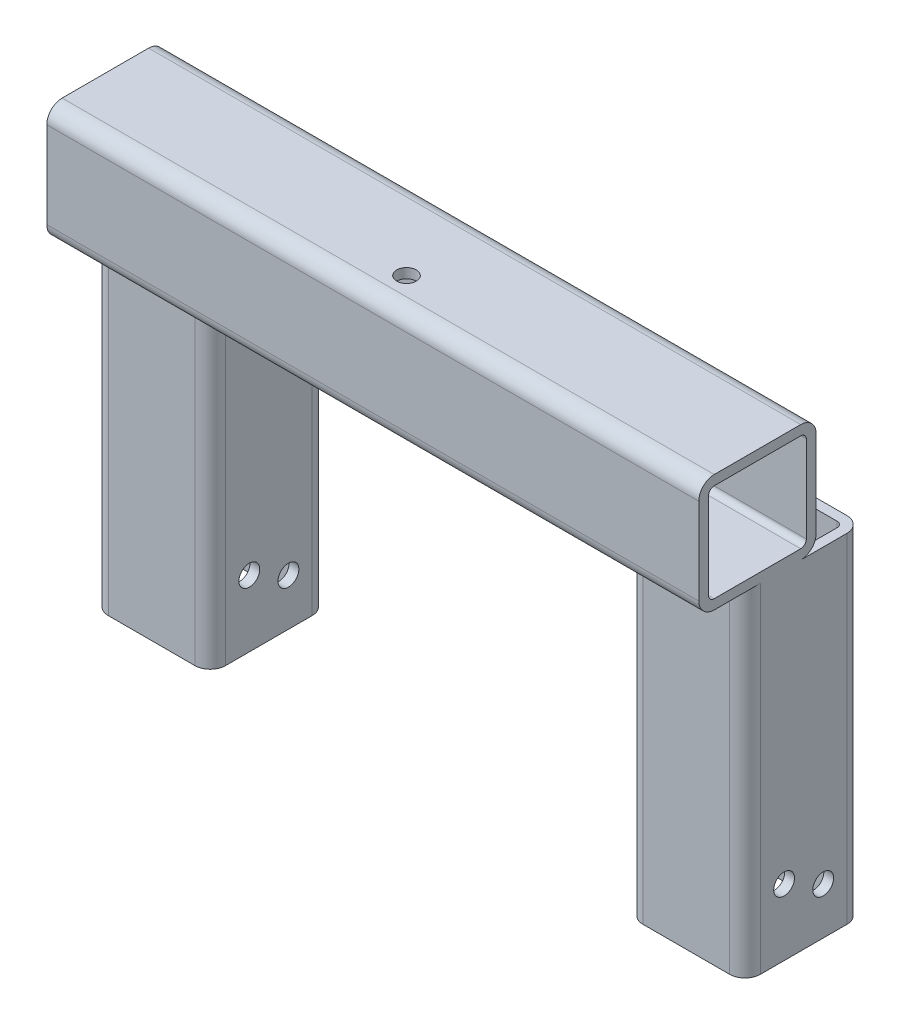
SolidWorks part; units mm, degrees
ref_plane "Front Plane" through (0, 0, 0) normal (0, 0, 1) x (1, 0, 0)
ref_plane "Top Plane" through (0, 0, 0) normal (0, 1, 0) x (1, 0, 0)
ref_plane "Right Plane" through (0, 0, 0) normal (1, 0, 0) x (0, 0, -1)
sketch "Sketch1" plane through (0, 0, 0) normal (0, 1, 0) x (1, 0, 0)
  line L0 (-14.05, 19.05) -> (14.05, 19.05)
  line L1 (19.05, 14.05) -> (19.05, -14.05)
  line L2 (-15.875, 14.05) -> (-15.875, -14.05)
  line L3 (-14.05, -15.875) -> (14.05, -15.875)
  line L4 (14.05, -19.05) -> (-14.05, -19.05)
  line L5 (-19.05, -14.05) -> (-19.05, 14.05)
  line L6 (0, 19.05) -> (0, -19.05) construction
  line L7 (-19.05, 0) -> (19.05, 0) construction
  line L8 (15.875, -14.05) -> (15.875, 14.05)
  line L9 (14.05, 15.875) -> (-14.05, 15.875)
  line L10 (0, 15.875) -> (0, -15.875) construction
  line L11 (-15.875, 0) -> (15.875, 0) construction
  arc A0 (14.05, 19.05) -> (19.05, 14.05) centre (14.05, 14.05) cw
  arc A1 (19.05, -14.05) -> (14.05, -19.05) centre (14.05, -14.05) cw
  arc A2 (-14.05, -19.05) -> (-19.05, -14.05) centre (-14.05, -14.05) cw
  arc A3 (-19.05, 14.05) -> (-14.05, 19.05) centre (-14.05, 14.05) cw
  arc A4 (-15.875, -14.05) -> (-14.05, -15.875) centre (-14.05, -14.05) ccw
  arc A5 (14.05, -15.875) -> (15.875, -14.05) centre (14.05, -14.05) ccw
  arc A6 (15.875, 14.05) -> (14.05, 15.875) centre (14.05, 14.05) ccw
  arc A7 (-14.05, 15.875) -> (-15.875, 14.05) centre (-14.05, 14.05) ccw
  point P33 (0, 0)
  dimension "D1" = 5
  dimension "D2" = 3.175
  dimension "D3" = 38.1
extrude "Boss-Extrude1" add sketch "Sketch1" along normal blind 110
ref_plane "Plane1" through (86.85, 0, 0) normal (1, 0, 0) x (0, 0, -1)
mirror "Mirror2" about plane through (86.85, 0, 0) normal (1, 0, 0) of bodies 101
sketch "Sketch2" plane through (86.85, 0, 0) normal (1, 0, 0) x (0, 0, -1)
  line L0 (-29.05, 148.1) -> (-0.95, 148.1)
  line L1 (4.05, 143.1) -> (4.05, 115)
  line L2 (-30.875, 143.1) -> (-30.875, 115)
  line L3 (-29.05, 113.175) -> (-0.95, 113.175)
  line L4 (-0.95, 110) -> (-29.05, 110)
  line L5 (-34.05, 115) -> (-34.05, 143.1)
  line L6 (-15, 148.1) -> (-15, 110) construction
  line L7 (-34.05, 129.05) -> (4.05, 129.05) construction
  line L8 (0.875, 115) -> (0.875, 143.1)
  line L9 (-0.95, 144.925) -> (-29.05, 144.925)
  line L10 (-15, 144.925) -> (-15, 113.175) construction
  line L11 (-30.875, 129.05) -> (0.875, 129.05) construction
  line L12 (0, 0) -> (0, -17.0016) construction
  line L13 (14.05, 110) -> (-14.05, 110) construction
  arc A0 (-0.95, 148.1) -> (4.05, 143.1) centre (-0.95, 143.1) cw
  arc A1 (4.05, 115) -> (-0.95, 110) centre (-0.95, 115) cw
  arc A2 (-29.05, 110) -> (-34.05, 115) centre (-29.05, 115) cw
  arc A3 (-34.05, 143.1) -> (-29.05, 148.1) centre (-29.05, 143.1) cw
  arc A4 (-30.875, 115) -> (-29.05, 113.175) centre (-29.05, 115) ccw
  arc A5 (-0.95, 113.175) -> (0.875, 115) centre (-0.95, 115) ccw
  arc A6 (0.875, 143.1) -> (-0.95, 144.925) centre (-0.95, 143.1) ccw
  arc A7 (-29.05, 144.925) -> (-30.875, 143.1) centre (-29.05, 143.1) ccw
  dimension "D1" = 5
  dimension "D2" = 3.175
  dimension "D3" = 38.1
  dimension "D4" = 15
extrude "Boss-Extrude2" add sketch "Sketch2" along normal up to surface and the other way up to surface
sketch "Sketch3" plane through (0, 110, 0) normal (0, -1, 0) x (1, 0, 0)
  circle A0 centre (86.8, 23.05) radius 3.175
extrude "Cut-Extrude1" cut sketch "Sketch3" against normal up to surface (38.1 mm away) up to face at (86.85, 148.1, 15)
hole_wizard "1/4 Clearance Hole1" positions "Sketch4" profile "Sketch5" hole size "1/4" standard "ANSI Inch" end condition through all
sketch "Sketch4" plane through (-19.05, 0, 0) normal (-1, 0, 0) x (0, 0, 1)
  line L0 (-14.05, 0) -> (14.05, 0) construction
  point P0 (-6.35, 15.24)
  point P2 (6.35, 21.59)
  dimension "D1" = 15.24
  dimension "D2" = 12.7
  dimension "D3" = 6.35
  dimension "D4" = 6.35
sketch "Sketch5" plane through (-19.05, 15.24, -6.35) normal (0, 1, 0) x (0, 0, 1)
  line L0 (0, 0) -> (0, 211.8)
  line L1 (0, 211.8) -> (3.3782, 211.8)
  line L2 (3.3782, 211.8) -> (3.3782, 0)
  line L5 (3.3782, 0) -> (0, 0)
  line L11 (0, -6.35) -> (0, 107.95) construction
  dimension "Thru Hole Dia." = 6.7564
  dimension "Thru Hole Depth" = 211.8
